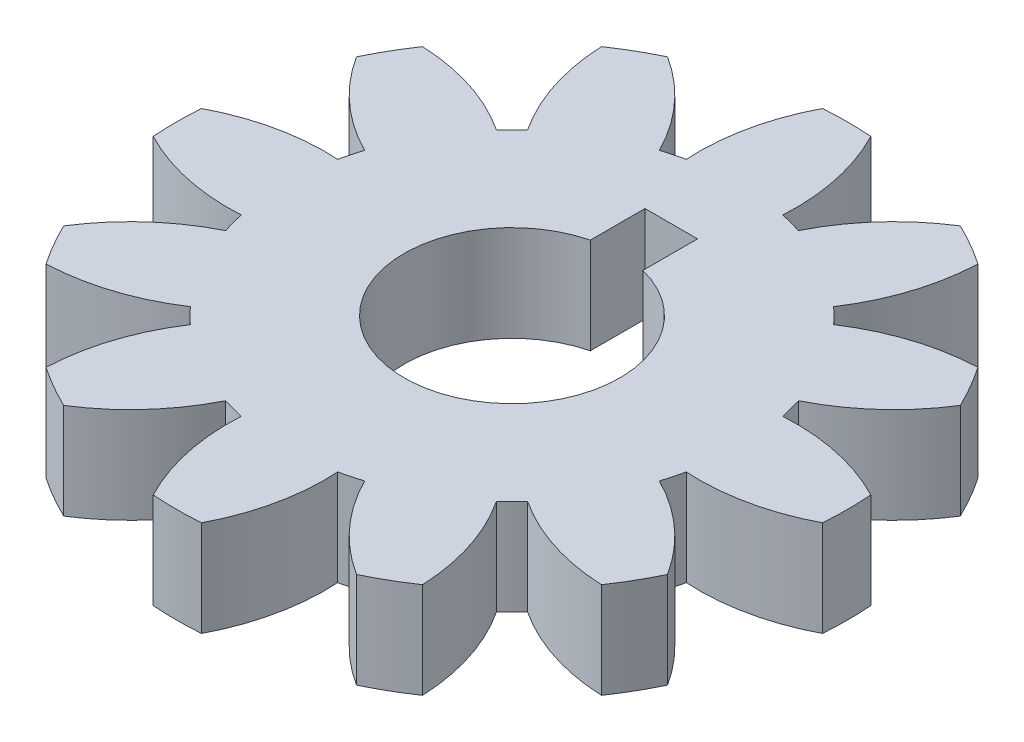
SolidWorks part; units mm, degrees
ref_plane "前视基准面" through (0, 0, 0) normal (0, 0, 1) x (1, 0, 0)
ref_plane "上视基准面" through (0, 0, 0) normal (0, 1, 0) x (1, 0, 0)
ref_plane "右视基准面" through (0, 0, 0) normal (1, 0, 0) x (0, 0, -1)
sketch "草图1" plane through (0, 0, 0) normal (0, 1, 0) x (1, 0, 0)
  line L0 (-12.86, 0) -> (15.5874, 0) construction
  line L1 (0, 12.5955) -> (0, -11.8859) construction
  circle A0 centre (0, 0) radius 12 construction
  arc A1 (1.0071, 13.9637) -> (-1.0071, 13.9637) centre (0, 0) ccw
  arc A2 (-2.0122, 9.2844) -> (-2.8996, 9.0467) centre (0, 0) ccw
  arc A3 (-2.0122, 9.2844) -> (-1.0071, 13.9637) centre (6.9003, 9.8177) cw
  arc A4 (2.0122, 9.2844) -> (1.0071, 13.9637) centre (-6.9003, 9.8177) ccw
  arc A5 (7.8541, 11.5894) -> (6.1097, 12.5965) centre (0, 0) ccw
  arc A6 (6.3849, 7.0344) -> (7.8541, 11.5894) centre (-1.067, 11.9525) ccw
  arc A7 (2.8996, 9.0467) -> (6.1097, 12.5965) centre (10.8846, 5.0522) cw
  arc A8 (12.5965, 6.1097) -> (11.5894, 7.8541) centre (0, 0) ccw
  arc A9 (9.0467, 2.8996) -> (12.5965, 6.1097) centre (5.0522, 10.8846) ccw
  arc A10 (7.0344, 6.3849) -> (11.5894, 7.8541) centre (11.9525, -1.067) cw
  arc A11 (13.9637, -1.0071) -> (13.9637, 1.0071) centre (0, 0) ccw
  arc A12 (9.2844, -2.0122) -> (13.9637, -1.0071) centre (9.8177, 6.9003) ccw
  arc A13 (9.2844, 2.0122) -> (13.9637, 1.0071) centre (9.8177, -6.9003) cw
  arc A14 (11.5894, -7.8541) -> (12.5965, -6.1097) centre (0, 0) ccw
  arc A15 (7.0344, -6.3849) -> (11.5894, -7.8541) centre (11.9525, 1.067) ccw
  arc A16 (9.0467, -2.8996) -> (12.5965, -6.1097) centre (5.0522, -10.8846) cw
  arc A17 (6.1097, -12.5965) -> (7.8541, -11.5894) centre (0, 0) ccw
  arc A18 (2.8996, -9.0467) -> (6.1097, -12.5965) centre (10.8846, -5.0522) ccw
  arc A19 (6.3849, -7.0344) -> (7.8541, -11.5894) centre (-1.067, -11.9525) cw
  arc A20 (-1.0071, -13.9637) -> (1.0071, -13.9637) centre (0, 0) ccw
  arc A21 (-2.0122, -9.2844) -> (-1.0071, -13.9637) centre (6.9003, -9.8177) ccw
  arc A22 (2.0122, -9.2844) -> (1.0071, -13.9637) centre (-6.9003, -9.8177) cw
  arc A23 (-7.8541, -11.5894) -> (-6.1097, -12.5965) centre (0, 0) ccw
  arc A24 (-6.3849, -7.0344) -> (-7.8541, -11.5894) centre (1.067, -11.9525) ccw
  arc A25 (-2.8996, -9.0467) -> (-6.1097, -12.5965) centre (-10.8846, -5.0522) cw
  arc A26 (-12.5965, -6.1097) -> (-11.5894, -7.8541) centre (0, 0) ccw
  arc A27 (-9.0467, -2.8996) -> (-12.5965, -6.1097) centre (-5.0522, -10.8846) ccw
  arc A28 (-7.0344, -6.3849) -> (-11.5894, -7.8541) centre (-11.9525, 1.067) cw
  arc A29 (-13.9637, 1.0071) -> (-13.9637, -1.0071) centre (0, 0) ccw
  arc A30 (-9.2844, 2.0122) -> (-13.9637, 1.0071) centre (-9.8177, -6.9003) ccw
  arc A31 (-9.2844, -2.0122) -> (-13.9637, -1.0071) centre (-9.8177, 6.9003) cw
  arc A32 (-11.5894, 7.8541) -> (-12.5965, 6.1097) centre (0, 0) ccw
  arc A33 (-7.0344, 6.3849) -> (-11.5894, 7.8541) centre (-11.9525, -1.067) ccw
  arc A34 (-9.0467, 2.8996) -> (-12.5965, 6.1097) centre (-5.0522, 10.8846) cw
  arc A35 (-6.1097, 12.5965) -> (-7.8541, 11.5894) centre (0, 0) ccw
  arc A36 (-2.8996, 9.0467) -> (-6.1097, 12.5965) centre (-10.8846, 5.0522) ccw
  arc A37 (-6.3849, 7.0344) -> (-7.8541, 11.5894) centre (1.067, 11.9525) cw
  arc A38 (2.8996, 9.0467) -> (2.0122, 9.2844) centre (0, 0) ccw
  arc A39 (7.0344, 6.3849) -> (6.3849, 7.0344) centre (0, 0) ccw
  arc A40 (9.2844, 2.0122) -> (9.0467, 2.8996) centre (0, 0) ccw
  arc A41 (9.0467, -2.8996) -> (9.2844, -2.0122) centre (0, 0) ccw
  arc A42 (6.3849, -7.0344) -> (7.0344, -6.3849) centre (0, 0) ccw
  arc A43 (2.0122, -9.2844) -> (2.8996, -9.0467) centre (0, 0) ccw
  arc A44 (-2.8996, -9.0467) -> (-2.0122, -9.2844) centre (0, 0) ccw
  arc A45 (-7.0344, -6.3849) -> (-6.3849, -7.0344) centre (0, 0) ccw
  arc A46 (-9.2844, -2.0122) -> (-9.0467, -2.8996) centre (0, 0) ccw
  arc A47 (-9.0467, 2.8996) -> (-9.2844, 2.0122) centre (0, 0) ccw
  arc A48 (-6.3849, 7.0344) -> (-7.0344, 6.3849) centre (0, 0) ccw
  point P82 (0, 0)
  dimension "D1" = 12
  dimension "D2" = 14
extrude "凸台-拉伸1" add sketch "草图1" along normal blind 4 contours A6 A5 A7 A38 A4 A1 A3 A2 A36 A35 A37 A48 A33 A32 A34 A47 A30 A29 A31 A46 A27 A26 A28 A45 A24 A23 A25 A44 A21 A20 A22 A43 A18 A17 A19 A42 A15 A14 A16 A41 A12 A11 A13 A40 A9 A8 A10 A39
sketch "草图2" plane through (0, 4, 0) normal (0, 1, 0) x (1, 0, 0)
  line L0 (-5.2812, 0) -> (6.6309, 0) construction
  line L1 (0, 5.867) -> (0, -6.4476) construction
  line L2 (-1.0959, 4.3645) -> (-1.0959, 6.645)
  line L3 (-1.0959, 6.645) -> (1.0959, 6.645)
  line L4 (1.0959, 4.3645) -> (1.0959, 6.645)
  arc A1 (-1.0959, 4.3645) -> (1.0959, 4.3645) centre (0, 0) ccw
  point P12 (0, 6.645)
extrude "切除-拉伸1" cut sketch "草图2" against normal blind 4
